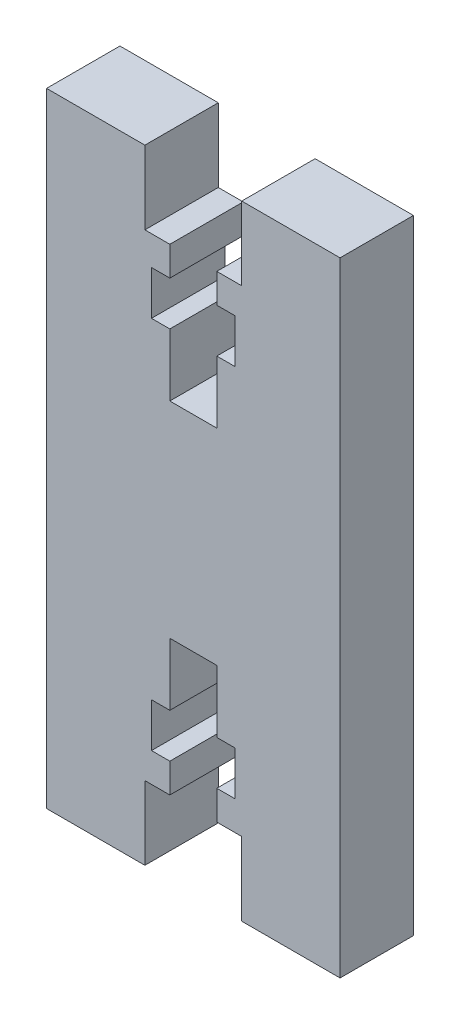
SolidWorks part; units mm, degrees
ref_plane "Plan de face" through (0, 0, 0) normal (0, 0, 1) x (1, 0, 0)
ref_plane "Plan de dessus" through (0, 0, 0) normal (0, 1, 0) x (1, 0, 0)
ref_plane "Plan de droite" through (0, 0, 0) normal (1, 0, 0) x (0, 0, -1)
sketch "Esquisse1" plane through (0, 0, 0) normal (0, 0, 1) x (1, 0, 0)
  line L0 (-12.9111, 37.8251) -> (-12.9111, -4.6749)
  line L1 (-12.9111, -4.6749) -> (-6.2111, -4.6749)
  line L2 (-6.2111, -4.6749) -> (-6.2111, 0.3251)
  line L3 (-6.2111, 0.3251) -> (-4.5111, 0.3251)
  line L4 (-4.5111, 0.3251) -> (-4.5111, 2.3218)
  line L5 (-4.5111, 2.3218) -> (-5.7611, 2.3218)
  line L6 (-5.7611, 2.3218) -> (-5.7611, 5.3218)
  line L7 (-5.7611, 5.3218) -> (-4.5111, 5.3218)
  line L8 (-4.5111, 5.3218) -> (-4.5111, 9.5751)
  line L9 (-4.5111, 9.5751) -> (-1.3111, 9.5751)
  line L10 (-1.3111, 9.5751) -> (-1.3111, 5.3218)
  line L11 (-1.3111, 5.3218) -> (-0.0611, 5.3218)
  line L12 (-0.0611, 5.3218) -> (-0.0611, 2.3218)
  line L13 (-0.0611, 2.3218) -> (-1.3111, 2.3218)
  line L14 (-1.3111, 2.3218) -> (-1.3111, 0.3251)
  line L15 (-1.3111, 0.3251) -> (0.3889, 0.3251)
  line L16 (0.3889, 0.3251) -> (0.3889, -4.6749)
  line L17 (0.3889, -4.6749) -> (7.0889, -4.6749)
  line L18 (7.0889, -4.6749) -> (7.0889, 37.8251)
  line L19 (-12.9111, 9.5751) -> (7.0889, 9.5751) construction
  line L20 (-12.9111, 16.5751) -> (7.0889, 16.5751) construction
  line L21 (-12.9111, 23.5751) -> (7.0889, 23.5751) construction
  line L22 (0.3889, 37.8251) -> (7.0889, 37.8251)
  line L23 (0.3889, 32.8251) -> (0.3889, 37.8251)
  line L24 (-1.3111, 32.8251) -> (0.3889, 32.8251)
  line L25 (-1.3111, 30.8284) -> (-1.3111, 32.8251)
  line L26 (-0.0611, 30.8284) -> (-1.3111, 30.8284)
  line L27 (-0.0611, 27.8284) -> (-0.0611, 30.8284)
  line L28 (-1.3111, 27.8284) -> (-0.0611, 27.8284)
  line L29 (-1.3111, 23.5751) -> (-1.3111, 27.8284)
  line L30 (-4.5111, 23.5751) -> (-1.3111, 23.5751)
  line L31 (-4.5111, 27.8284) -> (-4.5111, 23.5751)
  line L32 (-5.7611, 27.8284) -> (-4.5111, 27.8284)
  line L33 (-5.7611, 30.8284) -> (-5.7611, 27.8284)
  line L34 (-4.5111, 30.8284) -> (-5.7611, 30.8284)
  line L35 (-4.5111, 32.8251) -> (-4.5111, 30.8284)
  line L36 (-6.2111, 32.8251) -> (-4.5111, 32.8251)
  line L37 (-6.2111, 37.8251) -> (-6.2111, 32.8251)
  line L38 (-12.9111, 37.8251) -> (-6.2111, 37.8251)
  dimension "D1" = 21.25
  dimension "D2" = 21.25
  dimension "D3" = 20
  dimension "D4" = 6.7
  dimension "D5" = 6.7
  dimension "D6" = 3.2
  dimension "D7" = 1.7
  dimension "D8" = 7
  dimension "D9" = 3.2
  dimension "D10" = 0
  dimension "D11" = 5.7
  dimension "D12" = 1.25
  dimension "D13" = 1.9967
  dimension "D14" = 1.9967
  dimension "D15" = 3
  dimension "D16" = 3
  dimension "D17" = 5
  dimension "D18" = 5
extrude "Boss.-Extru.1" add sketch "Esquisse1" along normal blind 5
